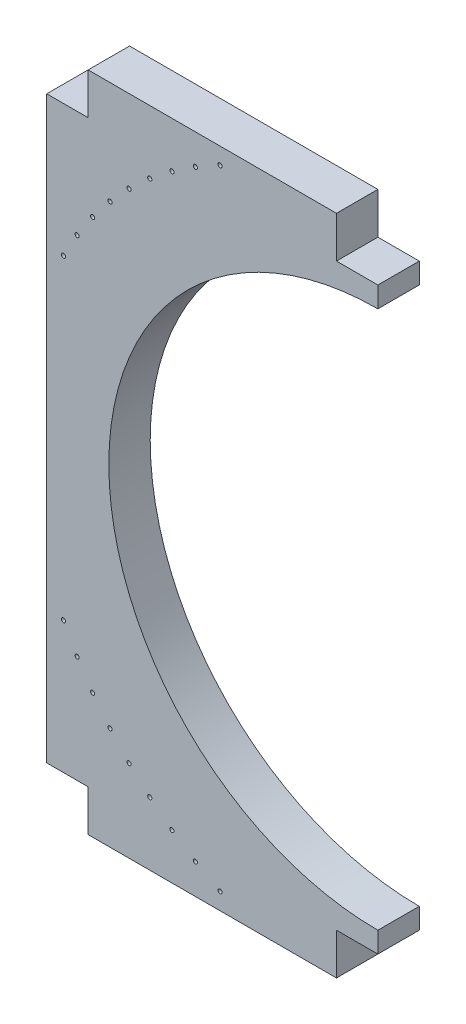
SolidWorks part; units mm, degrees
material "Balsa"
ref_plane "Plan de face" through (0, 0, 0) normal (0, 0, 1) x (1, 0, 0)
ref_plane "Plan de dessus" through (0, 0, 0) normal (0, 1, 0) x (1, 0, 0)
ref_plane "Plan de droite" through (0, 0, 0) normal (1, 0, 0) x (0, 0, -1)
sketch "Esquisse1" plane through (0, 0, 0) normal (0, 0, 1) x (1, 0, 0)
  line L0 (0, 40) -> (80, 40) construction
  line L1 (0, 80) -> (40, 80)
  line L2 (0, 80) -> (0, 0)
  line L3 (0, 0) -> (40, 0)
  line L5 (40, 80) -> (40, 0) construction
  line L6 (0, 80) -> (40, 40) construction
  line L8 (40, 80) -> (40, 72.5)
  line L9 (40, 0) -> (40, 7.5)
  arc A0 (40, 7.5) -> (40, 72.5) centre (40, 40) cw
  circle A1 centre (40, 40) radius 40 construction
  circle A2 centre (40, 40) radius 42.5 construction
  circle A3 centre (2.0185, 59.0698) radius 0.25
  circle A4 centre (7.6419, 67.5536) radius 0.25
  circle A5 centre (9.948, 70.052) radius 0.25
  circle A6 centre (3.6645, 62.0449) radius 0.25
  circle A7 centre (5.5429, 64.8789) radius 0.25
  circle A8 centre (20.9302, 77.9815) radius 0.25
  circle A9 centre (17.9551, 76.3355) radius 0.25
  circle A10 centre (15.1211, 74.4571) radius 0.25
  circle A11 centre (12.4464, 72.3581) radius 0.25
  circle A30 centre (12.4464, 7.6419) radius 0.25
  circle A31 centre (15.1211, 5.5429) radius 0.25
  circle A32 centre (17.9551, 3.6645) radius 0.25
  circle A33 centre (20.9302, 2.0185) radius 0.25
  circle A34 centre (5.5429, 15.1211) radius 0.25
  circle A35 centre (3.6645, 17.9551) radius 0.25
  circle A36 centre (9.948, 9.948) radius 0.25
  circle A37 centre (7.6419, 12.4464) radius 0.25
  circle A38 centre (2.0185, 20.9302) radius 0.25
  point P22 (40, 40)
  dimension "D3" = 32.5
  dimension "D4" = 85
  dimension "D5" = 40
  dimension "D7" = 0.5
  dimension "D9" = 3.4
  dimension "D2" = 80
  dimension "D10" = 3.4
  dimension "D11" = 3.4
  dimension "D12" = 3.4
extrude "Boss.-Extru.1" add sketch "Esquisse1" along normal blind 5
sketch "Esquisse2" plane through (0, 0, 5) normal (0, 0, 1) x (1, 0, 0)
  line L0 (0, 0) -> (40, 0) construction
  line L1 (0, 0) -> (5, 0)
  line L2 (0, 0) -> (0, 5)
  line L3 (0, 5) -> (5, 5)
  line L4 (5, 0) -> (5, 5)
  line L5 (35, 5) -> (40, 5)
  line L6 (35, 5) -> (35, 0)
  line L7 (35, 0) -> (40, 0)
  line L8 (40, 5) -> (40, 0)
  line L9 (0, 40) -> (40, 40) construction
  line L10 (0, 80) -> (0, 0) construction
  line L11 (40, 75) -> (40, 80)
  line L12 (35, 80) -> (40, 80)
  line L13 (35, 75) -> (35, 80)
  line L14 (35, 75) -> (40, 75)
  line L15 (5, 80) -> (5, 75)
  line L16 (0, 75) -> (5, 75)
  line L17 (0, 80) -> (0, 75)
  line L18 (0, 80) -> (5, 80)
  line L19 (40, 0) -> (40, 7.5) construction
  dimension "D1" = 5
  dimension "D2" = 5
  dimension "D3" = 5
extrude "Enlèv. mat.-Extru.1" cut sketch "Esquisse2" against normal blind 5
